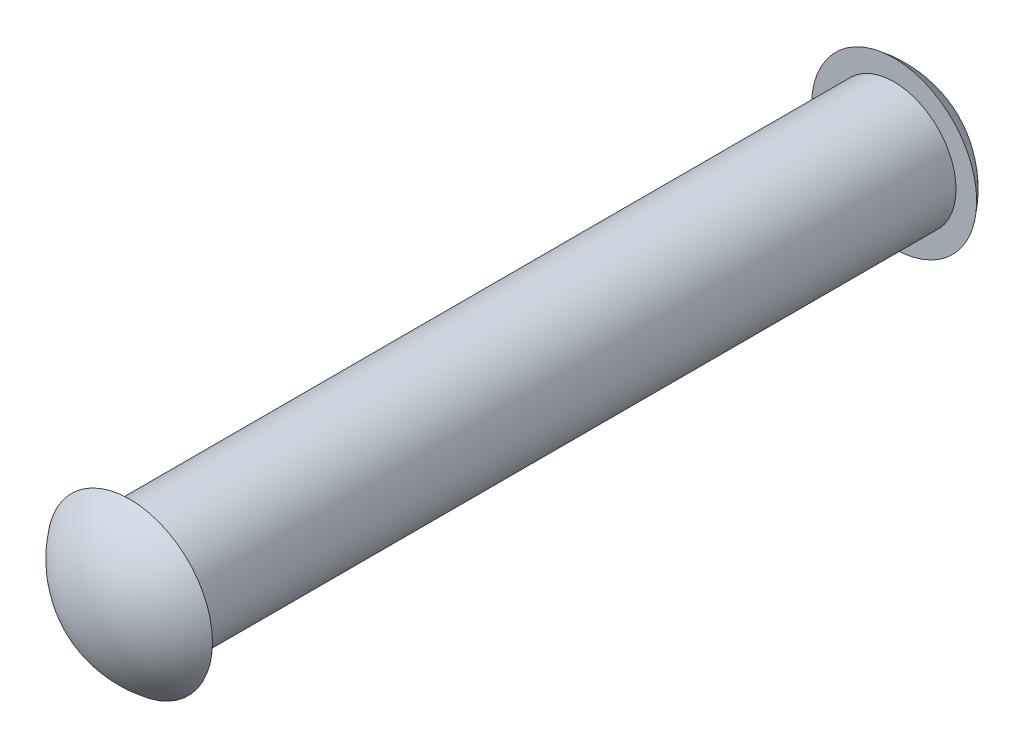
SolidWorks part; units mm, degrees
ref_plane "Alzado" through (0, 0, 0) normal (0, 0, 1) x (1, 0, 0)
ref_plane "Planta" through (0, 0, 0) normal (0, 1, 0) x (1, 0, 0)
ref_plane "Vista lateral" through (0, 0, 0) normal (1, 0, 0) x (0, 0, -1)
sketch "Croquis1" plane through (0, 0, 0) normal (0, 0, 1) x (1, 0, 0)
  circle A0 centre (31.8301, 0) radius 3
  circle A1 centre (31.8301, 0) radius 3 construction
extrude "Saliente-Extruir1" add sketch "Croquis1" against normal up to surface (37 mm away)
sketch "Croquis2" plane through (0, 0, 0) normal (0, 1, 0) x (1, 0, 0)
  line L0 (31.8301, 0) -> (31.8301, -2)
  line L1 (28.8301, 0) -> (34.8301, 0) construction
  line L2 (31.8301, 0) -> (39.3301, 0) construction
  line L3 (35.8301, 0) -> (31.8301, 0)
  arc A0 (31.8301, -2) -> (35.8301, 0) centre (31.8301, 3) ccw
  dimension "D1" = 2
  dimension "D2" = 4
ref_plane "Plano1" through (0, 0, -18.5) normal (0, 0, 1) x (1, 0, 0)
revolve "Revolución1" add sketch "Croquis2" angle 360 about L0
mirror "Simetría1" about plane through (0, 0, -18.5) normal (0, 0, 1) of "Revolución1"
